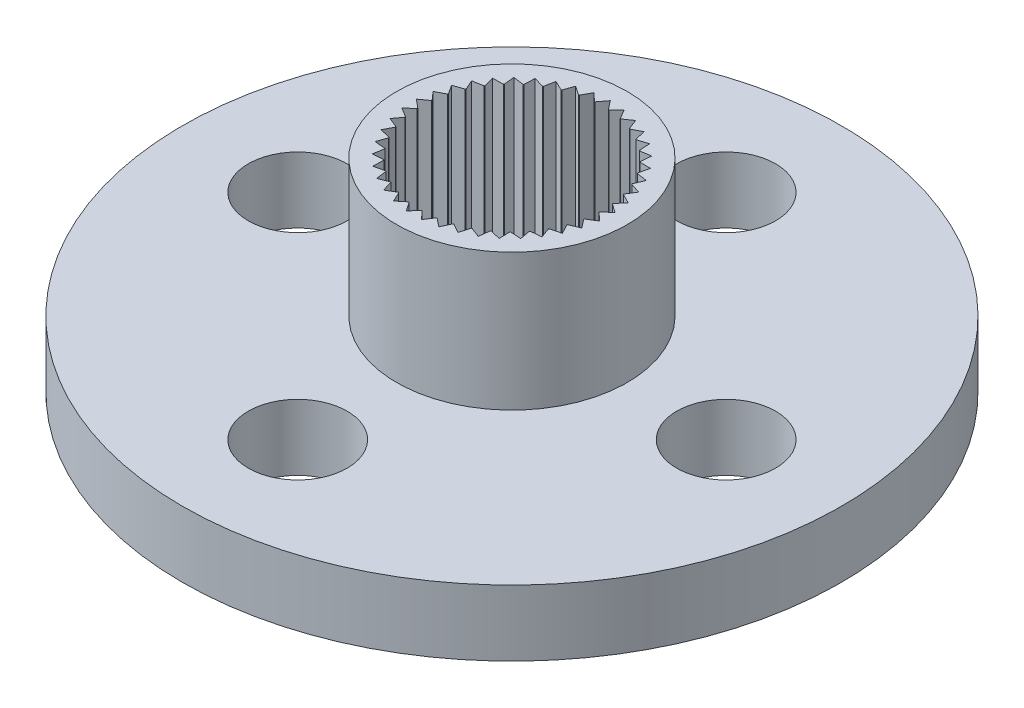
SolidWorks part; units mm, degrees
ref_plane "Front Plane" through (0, 0, 0) normal (0, 0, 1) x (1, 0, 0)
ref_plane "Top Plane" through (0, 0, 0) normal (0, 1, 0) x (1, 0, 0)
ref_plane "Right Plane" through (0, 0, 0) normal (1, 0, 0) x (0, 0, -1)
sketch "Sketch1" plane through (0, 0, 0) normal (0, 1, 0) x (1, 0, 0)
  line L0 (0, 0) -> (0, 4.1296) construction
  line L1 (0, 0) -> (4.0145, 0) construction
  circle A0 centre (0, 0) radius 10
  circle A1 centre (0, 0) radius 1.5
  circle A2 centre (-6.5, 0) radius 1.5
  circle A3 centre (0, -6.5) radius 1.5
  circle A4 centre (6.5, 0) radius 1.5
  circle A5 centre (0, 6.5) radius 1.5
  dimension "D1" = 20
  dimension "D2" = 3
  dimension "D3" = 3
  dimension "D4" = 3
  dimension "D5" = 6.5
  dimension "D6" = 6.5
extrude "Boss-Extrude1" add sketch "Sketch1" along normal blind 2
sketch "Sketch2" plane through (0, 2, 0) normal (0, 1, 0) x (1, 0, 0)
  circle A0 centre (0, 0) radius 3
  circle A1 centre (0, 0) radius 3.5
  dimension "D1" = 6
  dimension "D2" = 7
extrude "Boss-Extrude2" add sketch "Sketch2" along normal blind 4.15
sketch "Sketch5" plane through (0, 6.15, 0) normal (0, 1, 0) x (1, 0, 0)
  line L0 (0, 0) -> (-2.9481, 0.5554) construction
  line L1 (-2.9481, 0.5554) -> (-2.7323, 0.3113)
  line L2 (-2.9481, 0.5554) -> (-2.6583, 0.7044)
  line L3 (-2.8288, 0.999) -> (-2.5196, 1.1019)
  line L4 (-2.8288, 0.999) -> (-2.6528, 0.7247)
  line L5 (-2.6431, 1.4191) -> (-2.3219, 1.4736)
  line L6 (-2.6431, 1.4191) -> (-2.5111, 1.1212)
  line L7 (-2.3956, 1.8059) -> (-2.0697, 1.8107)
  line L8 (-2.3956, 1.8059) -> (-2.3105, 1.4913)
  line L9 (-2.0918, 2.1504) -> (-1.769, 2.1055)
  line L10 (-2.0918, 2.1504) -> (-2.0558, 1.8266)
  line L11 (-1.739, 2.4445) -> (-1.4269, 2.3508)
  line L12 (-1.739, 2.4445) -> (-1.7529, 2.119)
  line L13 (-1.3455, 2.6814) -> (-1.0513, 2.5411)
  line L14 (-1.3455, 2.6814) -> (-1.4089, 2.3617)
  line L15 (-0.9204, 2.8553) -> (-0.6511, 2.6718)
  line L16 (-0.9204, 2.8553) -> (-1.0318, 2.5491)
  line L17 (-0.4738, 2.9624) -> (-0.2356, 2.7399)
  line L18 (-0.4738, 2.9624) -> (-0.6306, 2.6767)
  line L19 (-0.016, 3) -> (0.1854, 2.7437)
  line L20 (-0.016, 3) -> (-0.2146, 2.7416)
  line L21 (0.4421, 2.9672) -> (0.602, 2.6833)
  line L22 (0.4421, 2.9672) -> (0.2064, 2.7422)
  line L23 (0.8899, 2.865) -> (1.0046, 2.56)
  line L24 (0.8899, 2.865) -> (0.6226, 2.6786)
  line L25 (1.3168, 2.6956) -> (1.3836, 2.3766)
  line L26 (1.3168, 2.6956) -> (1.0242, 2.5522)
  line L27 (1.7128, 2.463) -> (1.7301, 2.1375)
  line L28 (1.7128, 2.463) -> (1.4017, 2.3659)
  line L29 (2.0687, 2.1726) -> (2.0362, 1.8484)
  line L30 (2.0687, 2.1726) -> (1.7465, 2.1242)
  line L31 (2.3761, 1.8314) -> (2.2945, 1.5159)
  line L32 (2.3761, 1.8314) -> (2.0503, 1.8327)
  line L33 (2.6279, 1.4472) -> (2.499, 1.1479)
  line L34 (2.6279, 1.4472) -> (2.306, 1.4983)
  line L35 (2.818, 1.0291) -> (2.6449, 0.753)
  line L36 (2.818, 1.0291) -> (2.5077, 1.1287)
  line L37 (2.942, 0.5869) -> (2.7288, 0.3404)
  line L38 (2.942, 0.5869) -> (2.6506, 0.7327)
  line L39 (2.9971, 0.1309) -> (2.7488, -0.0801)
  line L40 (2.9971, 0.1309) -> (2.7314, 0.3195)
  line L41 (2.982, -0.3281) -> (2.7044, -0.4988)
  line L42 (2.982, -0.3281) -> (2.7481, -0.1012)
  line L43 (2.897, -0.7795) -> (2.5965, -0.9058)
  line L44 (2.897, -0.7795) -> (2.7005, -0.5195)
  line L45 (2.744, -1.2126) -> (2.4279, -1.2915)
  line L46 (2.744, -1.2126) -> (2.5895, -0.9257)
  line L47 (2.5268, -1.6172) -> (2.2022, -1.647)
  line L48 (2.5268, -1.6172) -> (2.4179, -1.3101)
  line L49 (2.2503, -1.984) -> (1.925, -1.9639)
  line L50 (2.2503, -1.984) -> (2.1896, -1.6638)
  line L51 (1.9211, -2.3042) -> (1.6027, -2.2347)
  line L52 (1.9211, -2.3042) -> (1.9099, -1.9786)
  line L53 (1.5468, -2.5705) -> (1.2428, -2.4532)
  line L54 (1.5468, -2.5705) -> (1.5855, -2.2469)
  line L55 (1.1363, -2.7765) -> (0.8537, -2.6141)
  line L56 (1.1363, -2.7765) -> (1.2239, -2.4626)
  line L57 (0.6991, -2.9174) -> (0.4447, -2.7138)
  line L58 (0.6991, -2.9174) -> (0.8337, -2.6206)
  line L59 (0.2456, -2.9899) -> (0.0252, -2.7499)
  line L60 (0.2456, -2.9899) -> (0.4239, -2.7171)
  line L61 (-0.2137, -2.9924) -> (-0.3948, -2.7215)
  line L62 (-0.2137, -2.9924) -> (0.0041, -2.75)
  line L63 (-0.668, -2.9247) -> (-0.8057, -2.6293)
  line L64 (-0.668, -2.9247) -> (-0.4157, -2.7184)
  line L65 (-1.1066, -2.7885) -> (-1.1976, -2.4755)
  line L66 (-1.1066, -2.7885) -> (-0.8258, -2.6231)
  line L67 (-1.5193, -2.5869) -> (-1.5614, -2.2637)
  line L68 (-1.5193, -2.5869) -> (-1.2165, -2.4663)
  line L69 (-1.8963, -2.3246) -> (-1.8887, -1.9988)
  line L70 (-1.8963, -2.3246) -> (-1.5787, -2.2517)
  line L71 (-2.229, -2.0079) -> (-2.1717, -1.6871)
  line L72 (-2.229, -2.0079) -> (-1.904, -1.9843)
  line L73 (-2.5094, -1.6441) -> (-2.4038, -1.3358)
  line L74 (-2.5094, -1.6441) -> (-2.1845, -1.6704)
  line L75 (-2.7309, -1.2418) -> (-2.5795, -0.9532)
  line L76 (-2.7309, -1.2418) -> (-2.4139, -1.3174)
  line L77 (-2.8885, -0.8104) -> (-2.6948, -0.5483)
  line L78 (-2.8885, -0.8104) -> (-2.5867, -0.9334)
  line L79 (-2.9783, -0.3599) -> (-2.7469, -0.1305)
  line L80 (-2.9783, -0.3599) -> (-2.6989, -0.5276)
  line L81 (-2.9984, 0.0989) -> (-2.7346, 0.2903)
  line L82 (-2.9984, 0.0989) -> (-2.7478, -0.1095)
  line L83 (-2.7346, 0.2903) -> (-2.7323, 0.3113)
  line L84 (-2.6583, 0.7044) -> (-2.6528, 0.7247)
  line L85 (-2.5196, 1.1019) -> (-2.5111, 1.1212)
  line L86 (-2.3219, 1.4736) -> (-2.3105, 1.4913)
  line L87 (-2.0697, 1.8107) -> (-2.0558, 1.8266)
  line L88 (-1.769, 2.1055) -> (-1.7529, 2.119)
  line L89 (-1.4269, 2.3508) -> (-1.4089, 2.3617)
  line L90 (-1.0513, 2.5411) -> (-1.0318, 2.5491)
  line L91 (-0.6511, 2.6718) -> (-0.6306, 2.6767)
  line L92 (-0.2356, 2.7399) -> (-0.2146, 2.7416)
  line L93 (0.1854, 2.7437) -> (0.2064, 2.7422)
  line L94 (0.602, 2.6833) -> (0.6226, 2.6786)
  line L95 (1.0046, 2.56) -> (1.0242, 2.5522)
  line L96 (1.3836, 2.3766) -> (1.4017, 2.3659)
  line L97 (1.7301, 2.1375) -> (1.7465, 2.1242)
  line L98 (2.0362, 1.8484) -> (2.0503, 1.8327)
  line L99 (2.2945, 1.5159) -> (2.306, 1.4983)
  line L100 (2.499, 1.1479) -> (2.5077, 1.1287)
  line L101 (2.6449, 0.753) -> (2.6506, 0.7327)
  line L102 (2.7288, 0.3404) -> (2.7314, 0.3195)
  line L103 (2.7488, -0.0801) -> (2.7481, -0.1012)
  line L104 (2.7044, -0.4988) -> (2.7005, -0.5195)
  line L105 (2.5965, -0.9058) -> (2.5895, -0.9257)
  line L106 (2.4279, -1.2915) -> (2.4179, -1.3101)
  line L107 (2.2022, -1.647) -> (2.1896, -1.6638)
  line L108 (1.925, -1.9639) -> (1.9099, -1.9786)
  line L109 (1.6027, -2.2347) -> (1.5855, -2.2469)
  line L110 (1.2428, -2.4532) -> (1.2239, -2.4626)
  line L111 (0.8537, -2.6141) -> (0.8337, -2.6206)
  line L112 (0.4447, -2.7138) -> (0.4239, -2.7171)
  line L113 (0.0252, -2.7499) -> (0.0041, -2.75)
  line L114 (-0.3948, -2.7215) -> (-0.4157, -2.7184)
  line L115 (-0.8057, -2.6293) -> (-0.8258, -2.6231)
  line L116 (-1.1976, -2.4755) -> (-1.2165, -2.4663)
  line L117 (-1.5614, -2.2637) -> (-1.5787, -2.2517)
  line L118 (-1.8887, -1.9988) -> (-1.904, -1.9843)
  line L119 (-2.1717, -1.6871) -> (-2.1845, -1.6704)
  line L120 (-2.4038, -1.3358) -> (-2.4139, -1.3174)
  line L121 (-2.5795, -0.9532) -> (-2.5867, -0.9334)
  line L122 (-2.6948, -0.5483) -> (-2.6989, -0.5276)
  line L123 (-2.7469, -0.1305) -> (-2.7478, -0.1095)
  circle A1 centre (0, 0) radius 3
  circle M3 centre (0, 0) radius 3
  dimension "D1" = 41
  dimension "D2" = 41
  dimension "D3" = 37.86
extrude "Boss-Extrude3" add sketch "Sketch5" against normal blind 4.15 contours L2 L84 L4 M3 | L3 L85 L6 M3 | L81 L83 L1 M3 | L79 L123 L82 M3 | L77 L122 L80 M3 | L75 L121 L78 M3 | L71 L119 L74 M3 | L73 L120 L76 M3 | L69 L118 L72 M3 | L67 L117 L70 M3 | L65 L116 L68 M3 | L63 L115 L66 M3 | L61 L114 L64 M3 | L59 L113 L62 M3 | L57 L112 L60 M3 | L55 L111 L58 M3 | L53 L110 L56 M3 | L51 L109 L54 M3 | L49 L108 L52 M3 | L47 L107 L50 M3 | L45 L106 L48 M3 | L43 L105 L46 M3 | L41 L104 L44 M3 | L39 L103 L42 M3 | L37 L102 L40 M3 | L35 L101 L38 M3 | L33 L100 L36 M3 | L31 L99 L34 M3 | L29 L98 L32 M3 | L27 L97 L30 M3 | L25 L96 L28 M3 | L23 L95 L26 M3 | L21 L94 L24 M3 | L19 L93 L22 M3 | L17 L92 L20 M3 | L15 L91 L18 M3 | L13 L90 L16 M3 | L11 L89 L14 M3 | L9 L88 L12 M3 | L7 L87 L10 M3 | L5 L86 L8 M3
